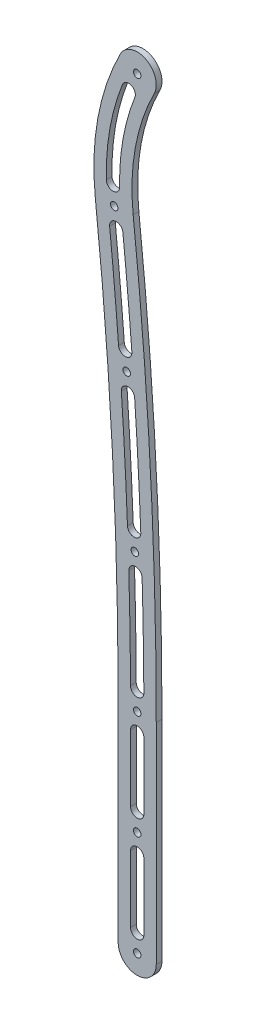
SolidWorks part; units mm, degrees
material "Thornel Mat VMA"
ref_plane "前视基准面" through (0, 0, 0) normal (0, 0, 1) x (1, 0, 0)
ref_plane "上视基准面" through (0, 0, 0) normal (0, 1, 0) x (1, 0, 0)
ref_plane "右视基准面" through (0, 0, 0) normal (1, 0, 0) x (0, 0, -1)
other "Configuration Table"
sketch "草图1" plane through (0, 0, 0) normal (0, 0, 1) x (1, 0, 0)
  line L0 (0, 0) -> (0, -400) construction
  line L1 (0, 0) -> (27.2394, -53.4604) construction
  line L2 (27.2394, -53.4604) -> (0, -53.4604) construction
  line L3 (0, 0) -> (9.5884, -2.8395) construction
  line L4 (-10, -290) -> (-10, -400)
  line L5 (10, -290) -> (10, -400)
  circle A0 centre (0, 0) radius 1.95
  circle A1 centre (27.2394, -53.4604) radius 30 construction
  circle A2 centre (0, -400) radius 1.95
  arc A3 (8.9219, -4.5165) -> (-8.9219, 4.5165) centre (0, 0) ccw
  arc A4 (-10, -400) -> (10, -400) centre (0, -400) ccw
  arc A6 (-8.9219, 4.5165) -> (-22.0156, -67.2701) centre (105.6058, -53.4604) ccw
  arc A7 (8.9219, -4.5165) -> (-2.1317, -65.1185) centre (105.6058, -53.4604) ccw
  arc A8 (-22.0156, -67.2701) -> (-10, -290) centre (-2080.3527, -290) cw
  arc A9 (-2.1317, -65.1185) -> (10, -290) centre (-2080.3527, -290) cw
  point P7 (0, -438.5439)
  point P8 (0, 0)
  point P12 (0, -425.7691)
  point P13 (0, -413.5529)
  point P23 (0, -401.4557)
  point P24 (0, -389.3463)
  point P25 (0, -375.1124)
  point P26 (-10, -278.2734)
  dimension "D3" = 60
  dimension "D5" = 3.9
  dimension "D6" = 20
  dimension "D8" = 20
  dimension "D9" = 20
  dimension "D2" = 60
  dimension "D4" = 27
  dimension "D7" = 73.504
  dimension "D10" = 110
  dimension "D11" = 400
extrude "凸台-拉伸2" add sketch "草图1" along normal blind 3 contours A6 A8 L4 A4 L5 A9 A7 A3 | A0 | A2
sketch "草图2" plane through (0, 0, 3) normal (0, 0, 1) x (1, 0, 0)
  line L0 (0, -400) -> (0, -290) construction
  line L1 (10, -290) -> (10, -400) construction
  arc A0 (0, 0) -> (-12.0736, -66.1943) centre (105.6058, -53.4604) ccw construction
  arc A1 (-12.0736, -66.1943) -> (0, -290) centre (-2080.3527, -290) cw construction
  arc A4 (10, -290) -> (-2.1317, -65.1185) centre (-2080.3527, -290) ccw construction
  arc A5 (8.9219, -4.5165) -> (-2.1317, -65.1185) centre (105.6058, -53.4604) ccw construction
sketch "草图3" plane through (0, 0, 3) normal (0, 0, 1) x (1, 0, 0)
  line L0 (0, -400) -> (0, -290) construction
  circle A0 centre (-12.0736, -66.1943) radius 1.95
  circle A1 centre (0, -290) radius 1.95
  circle A2 centre (0, -345) radius 1.95
  circle A3 centre (-5.5461, -138.1943) radius 1.95
  arc A4 (0, -290) -> (-12.0736, -66.1943) centre (-2080.3527, -290) ccw construction
  circle A5 centre (-1.2463, -218) radius 1.95
  dimension "D1" = 3.9
  dimension "D2" = 223.8057
  dimension "D4" = 72
  dimension "D3" = 72
extrude "切除-拉伸1" cut sketch "草图3" against normal through all
sketch "草图4" plane through (0, 0, 3) normal (0, 0, 1) x (1, 0, 0)
  line L0 (0, -300) -> (0, -335) construction
  line L1 (0, -400) -> (0, -290) construction
  line L2 (3.5, -300) -> (3.5, -335)
  line L3 (-3.5, -300) -> (-3.5, -335)
  line L4 (0, -355) -> (0, -390) construction
  line L5 (3.5, -355) -> (3.5, -390)
  line L6 (-3.5, -355) -> (-3.5, -390)
  line L7 (0, -300) -> (0, -355) construction
  arc A0 (-4.4932, -10) -> (-12.729, -56.1943) centre (105.6058, -53.4604) ccw construction
  arc A1 (0, 0) -> (-12.0736, -66.1943) centre (105.6058, -53.4604) ccw construction
  arc A2 (-7.7488, -8.7149) -> (-16.2281, -56.2752) centre (105.6058, -53.4604) ccw
  arc A3 (-1.2377, -11.2851) -> (-9.2299, -56.1135) centre (105.6058, -53.4604) ccw
  arc A4 (-1.2377, -11.2851) -> (-7.7488, -8.7149) centre (-4.4932, -10) ccw
  arc A5 (-16.2281, -56.2752) -> (-9.2299, -56.1135) centre (-12.729, -56.1943) ccw
  circle A6 centre (-12.0736, -66.1943) radius 1.95 construction
  arc A7 (-11.016, -76.1943) -> (-6.302, -128.1943) centre (-2080.3527, -290) cw construction
  arc A8 (0, -290) -> (-12.0736, -66.1943) centre (-2080.3527, -290) ccw construction
  arc A9 (-2.8126, -127.9221) -> (-7.5345, -75.8346) centre (-2080.3527, -290) ccw
  arc A10 (-9.7914, -128.4665) -> (-14.4974, -76.554) centre (-2080.3527, -290) ccw
  arc A11 (-9.7914, -128.4665) -> (-2.8126, -127.9221) centre (-6.302, -128.1943) ccw
  arc A12 (-7.5345, -75.8346) -> (-14.4974, -76.554) centre (-11.016, -76.1943) ccw
  arc A13 (-4.8387, -148.1943) -> (-1.6167, -208) centre (-2080.3527, -290) cw construction
  arc A14 (1.8806, -207.862) -> (-1.3468, -147.9558) centre (-2080.3527, -290) ccw
  arc A15 (-5.114, -208.138) -> (-8.3305, -148.4329) centre (-2080.3527, -290) ccw
  arc A16 (-5.114, -208.138) -> (1.8806, -207.862) centre (-1.6167, -208) ccw
  arc A17 (-1.3468, -147.9558) -> (-8.3305, -148.4329) centre (-4.8387, -148.1943) ccw
  arc A18 (-0.9241, -228) -> (-0.024, -280) centre (-2080.3527, -290) cw construction
  arc A19 (3.4759, -279.9832) -> (2.5744, -227.8957) centre (-2080.3527, -290) ccw
  arc A20 (-3.524, -280.0168) -> (-4.4225, -228.1043) centre (-2080.3527, -290) ccw
  arc A21 (-3.524, -280.0168) -> (3.4759, -279.9832) centre (-0.024, -280) ccw
  arc A22 (2.5744, -227.8957) -> (-4.4225, -228.1043) centre (-0.9241, -228) ccw
  arc A23 (3.5, -300) -> (-3.5, -300) centre (0, -300) ccw
  arc A24 (-3.5, -335) -> (3.5, -335) centre (0, -335) ccw
  circle A27 centre (0, -345) radius 1.95 construction
  circle A28 centre (0, -290) radius 1.95 construction
  circle A29 centre (-1.2463, -218) radius 1.95 construction
  circle A30 centre (-5.5461, -138.1943) radius 1.95 construction
  arc A31 (3.5, -355) -> (-3.5, -355) centre (0, -355) ccw
  arc A32 (-3.5, -390) -> (3.5, -390) centre (0, -390) ccw
  point P3 (-10.9231, -32.685)
  point P11 (-8.4958, -102.1795)
  point P25 (-3.0124, -178.0856)
  point P33 (-0.3116, -253.9972)
  point P41 (0, -317.5)
  point P58 (0, -405)
  point P59 (0, -372.5)
  point P68 (-4.88, -145.982)
  point P69 (0, 0)
  point P70 (-11.2458, -73.9816)
  point P71 (-4.88, -145.982)
  point P72 (-7.8057, -109.9549)
  point P73 (0, 0)
  point P74 (0, 0)
  point P75 (-1.6349, -207.5405)
  point P76 (0, -280.9978)
  point P77 (0, 0)
  point P78 (0, 0)
  dimension "D2" = 7
  dimension "D5" = 10
  dimension "D6" = 10
  dimension "D7" = 10
  dimension "D8" = 10
  dimension "D9" = 10
  dimension "D10" = 10
  dimension "D11" = 10
  dimension "D13" = 10
  dimension "D1" = 10
  dimension "D3" = 10
  dimension "D4" = 10
  dimension "D12" = 2
extrude "切除-拉伸2" cut sketch "草图4" against normal through all
